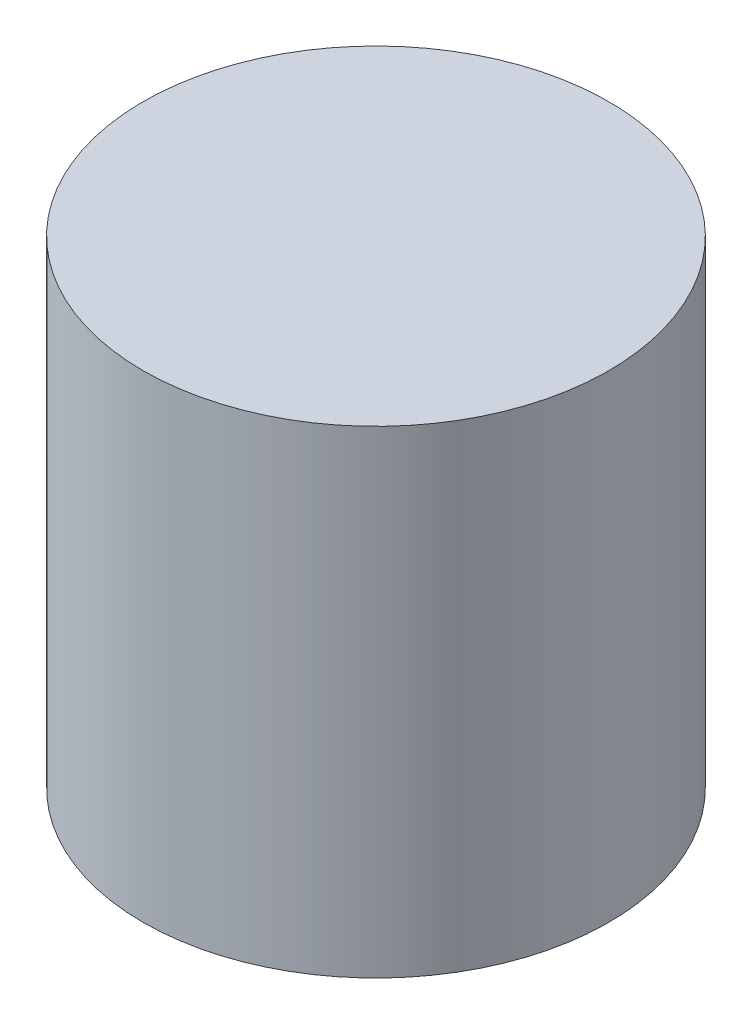
SolidWorks part; units mm, degrees
material "Pine"
ref_plane "Front Plane" through (0, 0, 0) normal (0, 0, 1) x (1, 0, 0)
ref_plane "Top Plane" through (0, 0, 0) normal (0, 1, 0) x (1, 0, 0)
ref_plane "Right Plane" through (0, 0, 0) normal (1, 0, 0) x (0, 0, -1)
sketch "Sketch1" plane through (0, 0, 0) normal (0, 1, 0) x (1, 0, 0)
  circle A0 centre (0, 0) radius 49.53
  dimension "D1" = 99.06
extrude "Boss-Extrude1" add sketch "Sketch1" along normal blind 101.6
